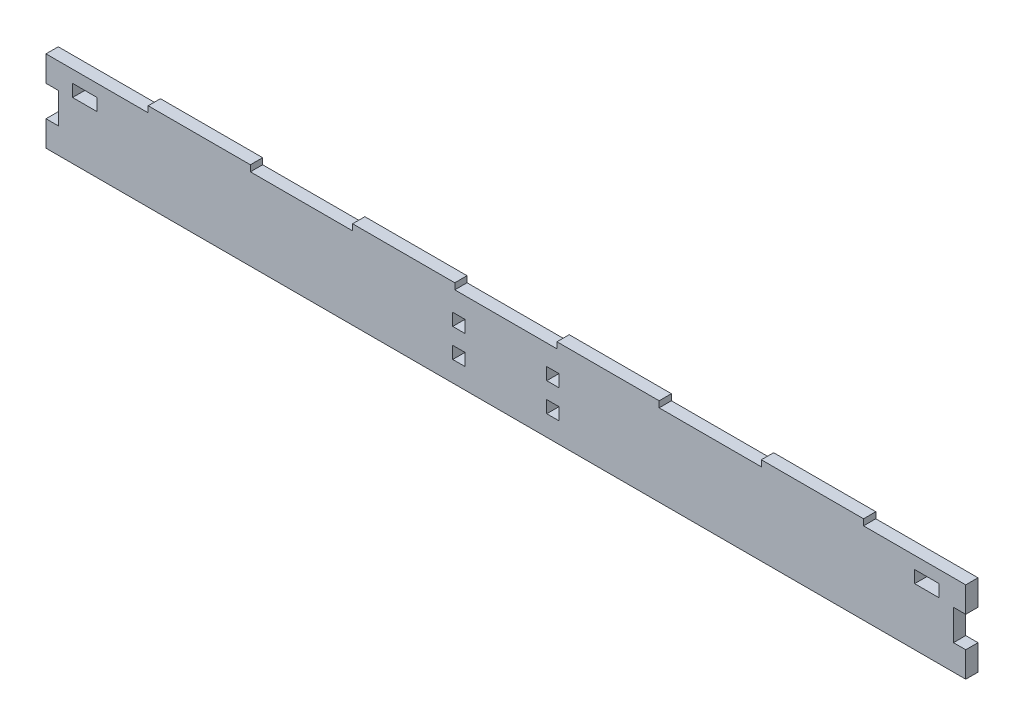
SolidWorks part; units mm, degrees
ref_plane "Спереди" through (0, 0, 0) normal (0, 0, 1) x (1, 0, 0)
ref_plane "Сверху" through (0, 0, 0) normal (0, 1, 0) x (1, 0, 0)
ref_plane "Справа" through (0, 0, 0) normal (1, 0, 0) x (0, 0, -1)
sketch "Эскиз1" plane through (0, 0, 0) normal (0, 0, 1) x (1, 0, 0)
  line L0 (100, 40) -> (150, 40)
  line L1 (0, 0) -> (450, 0)
  line L2 (0, 0) -> (0, 12.5)
  line L4 (450, 0) -> (450, 12.5)
  line L5 (0, 27.5) -> (6, 27.5)
  line L7 (0, 12.5) -> (6, 12.5)
  line L8 (6, 27.5) -> (6, 12.5)
  line L9 (450, 27.5) -> (444, 27.5)
  line L11 (450, 12.5) -> (444, 12.5)
  line L12 (444, 27.5) -> (444, 12.5)
  line L14 (50, 40) -> (50, 43)
  line L15 (50, 43) -> (100, 43)
  line L16 (100, 40) -> (100, 43)
  line L18 (150, 40) -> (150, 43)
  line L19 (150, 43) -> (200, 43)
  line L20 (200, 40) -> (200, 43)
  line L22 (250, 40) -> (250, 43)
  line L23 (250, 43) -> (300, 43)
  line L24 (300, 40) -> (300, 43)
  line L26 (350, 40) -> (350, 43)
  line L27 (350, 43) -> (400, 43)
  line L28 (400, 40) -> (400, 43)
  line L29 (200, 40) -> (250, 40)
  line L30 (300, 40) -> (350, 40)
  line L32 (0, 27.5) -> (0, 40)
  line L33 (450, 27.5) -> (450, 40)
  line L39 (13, 34) -> (25, 34)
  line L40 (13, 34) -> (13, 28)
  line L41 (13, 28) -> (25, 28)
  line L42 (25, 34) -> (25, 28)
  line L48 (437, 34) -> (425, 34)
  line L49 (437, 34) -> (437, 28)
  line L50 (437, 28) -> (425, 28)
  line L51 (425, 34) -> (425, 28)
  line L53 (0, 40) -> (50, 40)
  line L54 (400, 40) -> (450, 40)
  line L55 (245, 10) -> (205, 10) construction
  line L56 (251, 30) -> (245, 30)
  line L57 (251, 30) -> (251, 24)
  line L58 (251, 24) -> (245, 24)
  line L59 (245, 30) -> (245, 24)
  line L60 (251, 16) -> (245, 16)
  line L61 (251, 16) -> (251, 10)
  line L62 (251, 10) -> (245, 10)
  line L63 (245, 16) -> (245, 10)
  line L64 (205, 30) -> (199, 30)
  line L65 (205, 30) -> (205, 24)
  line L66 (205, 24) -> (199, 24)
  line L67 (199, 30) -> (199, 24)
  line L68 (205, 16) -> (199, 16)
  line L69 (205, 16) -> (205, 10)
  line L70 (205, 10) -> (199, 10)
  line L71 (199, 16) -> (199, 10)
  point P53 (225, 10)
  point P54 (225, 0)
  dimension "D1" = 450
  dimension "D2" = 40
  dimension "D3" = 50
  dimension "D4" = 50
  dimension "D5" = 50
  dimension "D6" = 50
  dimension "D7" = 50
  dimension "D8" = 50
  dimension "D9" = 50
  dimension "D10" = 50
  dimension "D11" = 12
  dimension "D12" = 15
  dimension "D13" = 12.5
  dimension "D14" = 6
  dimension "D15" = 6
  dimension "D16" = 6
  dimension "D17" = 7
  dimension "D18" = 6
  dimension "D19" = 3
  dimension "D20" = 12
  dimension "D21" = 7
  dimension "D22" = 6
  dimension "D23" = 6
  dimension "D24" = 40
  dimension "D25" = 6
  dimension "D26" = 6
  dimension "D27" = 10
  dimension "D28" = 8
extrude "Бобышка-Вытянуть1" add sketch "Эскиз1" along normal blind 6
